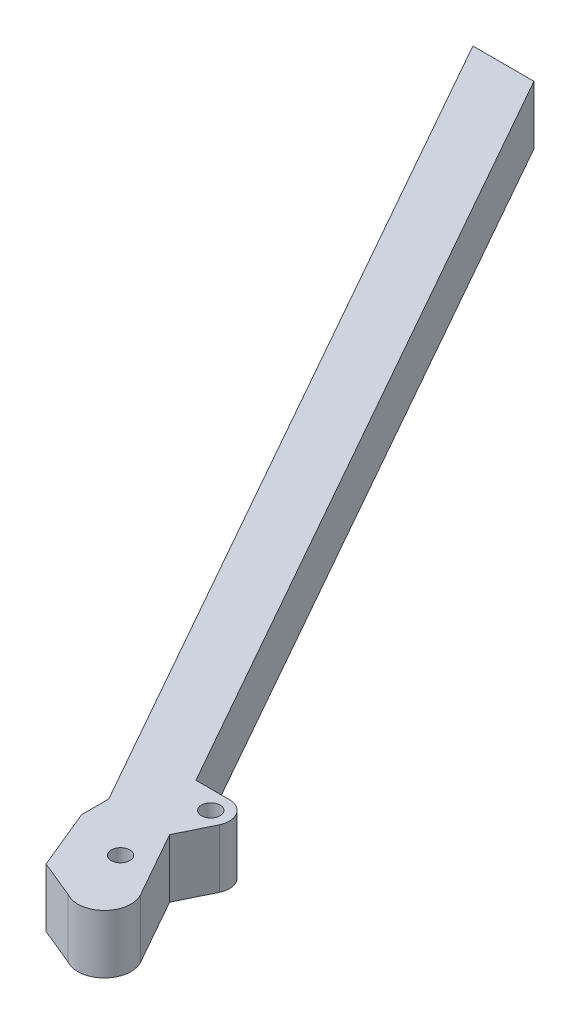
SolidWorks part; units mm, degrees
ref_plane "Alzado" through (0, 0, 0) normal (0, 0, 1) x (1, 0, 0)
ref_plane "Planta" through (0, 0, 0) normal (0, 1, 0) x (1, 0, 0)
ref_plane "Vista lateral" through (0, 0, 0) normal (1, 0, 0) x (0, 0, -1)
sketch "Croquis1" plane through (0, 0, 0) normal (0, 1, 0) x (1, 0, 0)
  line L0 (-6.9961, -3.1957) -> (-105.1763, 171.0474)
  line L1 (-105.1763, 171.0474) -> (-93.6981, 171.0474)
  line L2 (-93.6981, 171.0474) -> (-11.6927, 25.5102)
  line L3 (-11.6927, 25.5102) -> (-5.3937, 25.5102)
  line L4 (-2.2468, 20.4781) -> (-5.3109, 14.1844)
  line L6 (-5.3109, 14.1844) -> (1.716, 1.7134)
  arc A1 (-5.3937, 25.5102) -> (-2.2468, 20.4781) centre (-5.3937, 22.0102) cw
  arc A2 (1.716, 1.7134) -> (-6.9961, -3.1957) centre (-2.64, -0.7412) cw
  circle A3 centre (-5.3937, 22.0102) radius 1.75
  circle A4 centre (-6.5672, 6.2286) radius 1.75
  point P13 (0, 0)
  point P14 (0, 0)
  point P15 (-0.1855, -5.0972)
  point P16 (0, 0)
  point P17 (0, 0)
  point P18 (0, 0)
  point P19 (-11.6927, 25.5102)
  dimension "D1" = 3.5
  dimension "D2" = 3.5
  dimension "D7" = 3.5
  dimension "D3" = 200
  dimension "D4" = 10
  dimension "D5" = 5
  dimension "D6" = 13
  dimension "D8" = 13
  dimension "D9" = 7
extrude "Saliente-Extruir1" add sketch "Croquis1" along normal mid plane 11
sketch "Croquis3" plane through (0, 5.5, 0) normal (0, 1, 0) x (1, 0, 0)
  line L0 (-5.1508, -5.065) -> (-12.1508, -2.1957)
  line L3 (-105.1763, 171.0474) -> (-6.9961, -3.1957) construction
  line L4 (-16.8311, 14.2588) -> (-6.9961, -3.1957)
  line L5 (-12.1508, -2.1957) -> (-16.8379, 9.1781)
  line L6 (-16.8379, 9.1781) -> (-16.8311, 14.2588)
  line L10 (1.716, 1.7134) -> (-5.3109, 14.1844)
  line L11 (-5.3109, 14.1844) -> (-2.2468, 20.4781)
  line L12 (-5.3937, 25.5102) -> (-11.6927, 25.5102)
  line L13 (-11.6927, 25.5102) -> (-93.6981, 171.0474)
  line L14 (-93.6981, 171.0474) -> (-105.1763, 171.0474)
  line L15 (-105.1763, 171.0474) -> (-6.9961, -3.1957)
  line L16 (1.716, 1.7134) -> (-5.3109, 14.1844)
  line L17 (-5.3109, 14.1844) -> (-2.2468, 20.4781)
  line L18 (-5.3937, 25.5102) -> (-11.6927, 25.5102)
  line L19 (-11.6927, 25.5102) -> (-93.6981, 171.0474)
  line L20 (-93.6981, 171.0474) -> (-105.1763, 171.0474)
  line L21 (-105.1763, 171.0474) -> (-6.9961, -3.1957)
  arc A0 (-6.9961, -3.1957) -> (1.716, 1.7134) centre (-2.64, -0.7412) ccw construction
  arc A1 (-6.9961, -3.1957) -> (-2.64, -5.7412) centre (-2.64, -0.7412) ccw
  arc A3 (-6.9961, -3.1957) -> (1.716, 1.7134) centre (-2.64, -0.7412) ccw
  arc A4 (-2.2468, 20.4781) -> (-5.3937, 25.5102) centre (-5.3937, 22.0102) ccw
  arc A5 (-6.9961, -3.1957) -> (1.716, 1.7134) centre (-2.64, -0.7412) ccw
  arc A6 (-2.2468, 20.4781) -> (-5.3937, 25.5102) centre (-5.3937, 22.0102) ccw
  point P11 (0, 0)
  dimension "D2" = 4
  dimension "D3" = 7
  dimension "D4" = 2.5
  dimension "D5" = 9.9192
  dimension "D1" = 0
extrude "Saliente-Extruir2" add sketch "Croquis3" against normal blind 11
